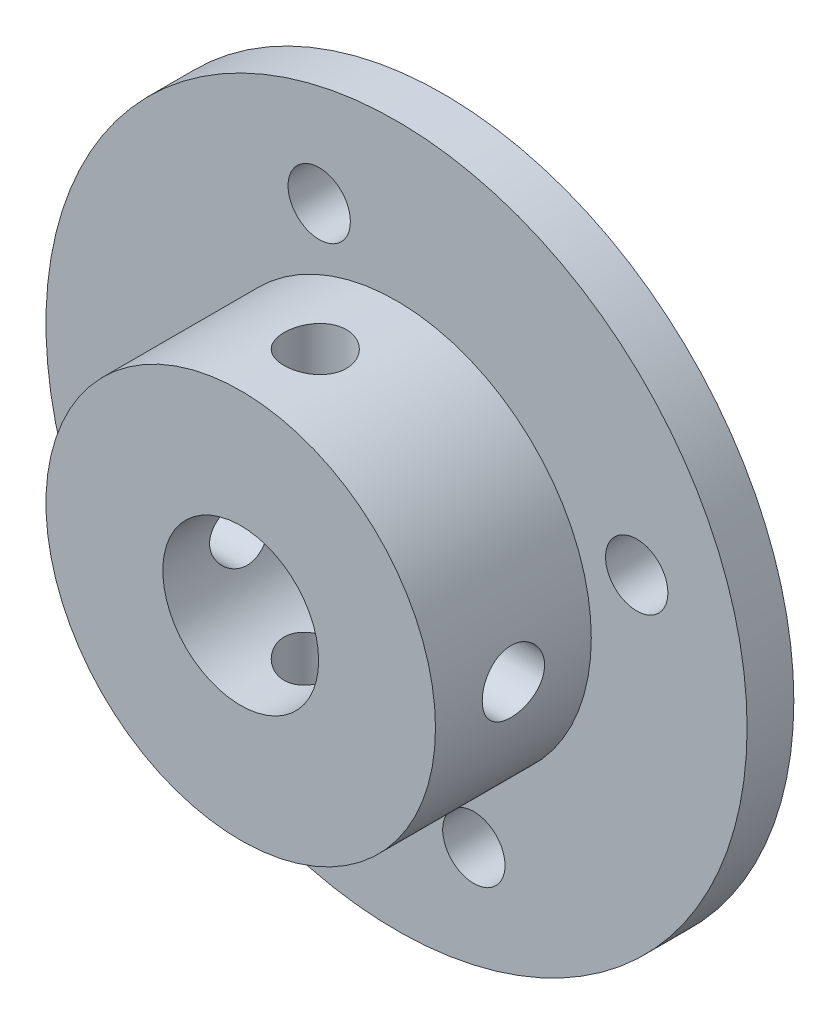
SolidWorks part; units mm, degrees
material "Bronce de aluminio"
ref_plane "Alzado" through (0, 0, 0) normal (0, 0, 1) x (1, 0, 0)
ref_plane "Planta" through (0, 0, 0) normal (0, 1, 0) x (1, 0, 0)
ref_plane "Vista lateral" through (0, 0, 0) normal (1, 0, 0) x (0, 0, -1)
sketch "Croquis1" plane through (0, 0, 0) normal (0, 0, 1) x (1, 0, 0)
  circle A0 centre (0, 0) radius 22.5
  dimension "D1" = 45
extrude "Saliente-Extruir1" add sketch "Croquis1" along normal blind 3
sketch "Croquis2" plane through (0, 0, 3) normal (0, 0, 1) x (1, 0, 0)
  circle A0 centre (0, 0) radius 12.5
  dimension "D1" = 25
extrude "Saliente-Extruir2" add sketch "Croquis2" along normal blind 10
sketch "Croquis3" plane through (0, 0, 13) normal (0, 0, 1) x (1, 0, 0)
  circle A0 centre (0, 0) radius 5
  dimension "D1" = 10
extrude "Cortar-Extruir1" cut sketch "Croquis3" against normal through all
sketch "Croquis4" plane through (0, 0, 3) normal (0, 0, 1) x (1, 0, 0)
  circle A0 centre (-4.9625, 15.4149) radius 2
  circle A1 centre (15.4149, 4.9625) radius 2
  circle A2 centre (4.9625, -15.4149) radius 2
  circle A3 centre (-15.4149, -4.9625) radius 2
  point P11 (0, 0)
  dimension "D2" = 4
  dimension "D1" = 4
extrude "Cortar-Extruir2" cut sketch "Croquis4" against normal through all
sketch "Croquis5" plane through (0, 0, 0) normal (1, 0, 0) x (0, 0, -1)
  line L0 (-13, 0) -> (-3, 0) construction
  line L1 (-13, 12.5) -> (-13, -12.5) construction
  line L2 (-3, 12.5) -> (-13, 12.5) construction
  line L3 (-13, -12.5) -> (-3, -12.5) construction
  line L4 (-3, 12.5) -> (-3, -12.5) construction
  circle A0 centre (-8, 0) radius 2
  dimension "D1" = 4
extrude "Cortar-Extruir3" cut sketch "Croquis5" against normal through all and the other way through all
sketch "Croquis6" plane through (0, 0, 0) normal (0, 1, 0) x (1, 0, 0)
  line L0 (0, -5.6068) -> (0, -10.8238) construction
  line L1 (-12.5, -3) -> (-12.5, -6) construction
  line L2 (12.5, -6) -> (12.5, -3) construction
  circle A0 centre (0, -8.2153) radius 2
  point P8 (0, -8.2153)
  dimension "D1" = 4
extrude "Cortar-Extruir4" cut sketch "Croquis6" against normal through all and the other way through all
